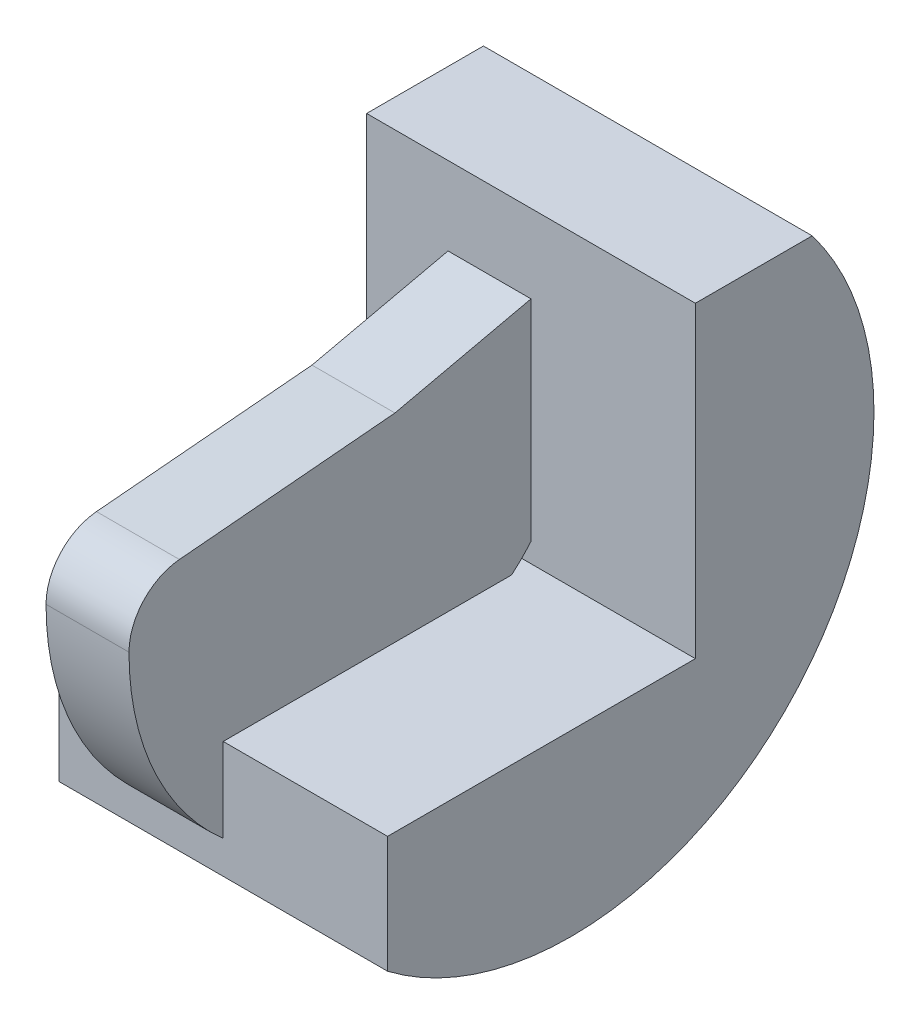
SolidWorks part; units mm, degrees
ref_plane "Front Plane" through (0, 0, 0) normal (0, 0, 1) x (1, 0, 0)
ref_plane "Top Plane" through (0, 0, 0) normal (0, 1, 0) x (1, 0, 0)
ref_plane "Right Plane" through (0, 0, 0) normal (1, 0, 0) x (0, 0, -1)
sketch "Sketch1" plane through (48.18, 0, 0) normal (1, 0, 0) x (0, 0, -1)
  line B0 (0, 0) -> (9, 0) construction
  line B1 (17.45, -13.265) -> (9, -13.265)
  line B2 (17.45, -13.265) -> (17.45, 13.265)
  line B3 (17.45, 13.265) -> (9, 13.265)
  line B4 (9, -13.265) -> (9, 13.265)
  line B5 (0, 0) -> (0, -9) construction
  line B6 (-13.265, -17.45) -> (-13.265, -9)
  line B7 (-13.265, -17.45) -> (13.265, -17.45)
  line B8 (13.265, -17.45) -> (13.265, -9)
  line B9 (-13.265, -9) -> (13.265, -9)
sketch_block_instance "Block1-1"
sketch_block "Block1"
sketch_block_instance "Block1-2"
sketch "Sketch2" plane through (36.29, 0, 0) normal (1, 0, 0) x (0, 0, -1)
  line B0 (0, 0) -> (9, 0) construction
  line B1 (9, -7.595) -> (9, 7.595)
  line B2 (9, 7.595) -> (-1.1969, 5.2862)
  line B3 (-5.3988, -0.4786) -> (-3.9844, -16.4332)
  line B4 (3.9844, -16.4332) -> (4.7679, -7.595)
  line B5 (4.7679, -7.595) -> (9, -7.595)
  arc B6 (-1.1969, 5.2862) -> (-5.3988, -0.4786) centre (0, 0) ccw
  arc B7 (-3.9844, -16.4332) -> (3.9844, -16.4332) centre (0, -16.08) ccw
  line B8 (0, 0) -> (0, -9) construction
  line B9 (-7.595, -9) -> (7.595, -9)
  line B10 (7.595, -9) -> (5.2862, 1.1969)
  line B11 (-0.4786, 5.3988) -> (-16.4332, 3.9844)
  line B12 (-16.4332, -3.9844) -> (-7.595, -4.7679)
  line B13 (-7.595, -4.7679) -> (-7.595, -9)
  arc B14 (5.2862, 1.1969) -> (-0.4786, 5.3988) centre (0, 0) ccw
  arc B15 (-16.4332, 3.9844) -> (-16.4332, -3.9844) centre (-16.08, 0) ccw
sketch_block_instance "Block3-1"
sketch_block "Block3"
sketch_block_instance "Block3-3"
sketch "Sketch3" plane through (48.18, 0, 0) normal (1, 0, 0) x (0, 0, -1)
  line L0 (17.45, -13.265) -> (17.45, 13.265) construction
  line L1 (17.45, 13.265) -> (9, 13.265) construction
  line L2 (17.45, -13.265) -> (17.45, 13.265) construction
  line L3 (17.45, 13.265) -> (9, 13.265)
  line L4 (9, -13.265) -> (9, 13.265) construction
  line L5 (-13.265, -9) -> (13.265, -9) construction
  line L6 (-13.265, -17.45) -> (-13.265, -9) construction
  line L7 (-13.265, -17.45) -> (13.265, -17.45) construction
  line L8 (9, -9) -> (9, 13.265)
  line L9 (-13.265, -9) -> (9, -9)
  line L10 (-13.265, -17.45) -> (-13.265, -9)
  line L11 (-13.265, -17.45) -> (13.265, -17.45) construction
  arc A0 (17.45, -13.265) -> (13.265, -17.45) centre (0, 0) cw construction
  arc A1 (17.45, 13.265) -> (-13.265, -17.45) centre (0, 0) cw
extrude "Boss-Extrude1" add sketch "Sketch3" against normal up to surface (23.78 mm away)
sketch "Sketch4" plane through (36.29, 0, 0) normal (1, 0, 0) x (0, 0, -1)
  line L0 (3.9844, -16.4332) -> (4.7679, -7.595) construction
  line L5 (-0.4786, 5.3988) -> (-16.4332, 3.9844) construction
  line L6 (9, 7.595) -> (-1.1969, 5.2862) construction
  line L10 (3.9844, -16.4332) -> (4.6434, -9)
  line L15 (-0.8416, 5.3666) -> (-16.4332, 3.9844)
  line L16 (9, 7.595) -> (-0.8416, 5.3666)
  line L20 (4.6434, -9) -> (7.595, -9)
  line L21 (-7.595, -9) -> (7.595, -9) construction
  arc A0 (-3.9844, -16.4332) -> (3.9844, -16.4332) centre (0, -16.08) ccw construction
  arc A1 (-16.4332, 3.9844) -> (-16.4332, -3.9844) centre (-16.08, 0) ccw construction
  arc A2 (-1.1969, 5.2862) -> (-5.3988, -0.4786) centre (0, 0) ccw construction
  arc A4 (0, -20.08) -> (3.9844, -16.4332) centre (0, -16.08) ccw
  arc A5 (-16.4332, 3.9844) -> (-20.08, 0) centre (-16.08, 0) ccw
  arc A8 (-20.08, 0) -> (0, -20.08) centre (0, 0) ccw
  arc A9 (9, 7.595) -> (7.595, -9) centre (0, 0) cw
extrude "Boss-Extrude2" add sketch "Sketch4" against normal up to surface (6 mm away)
